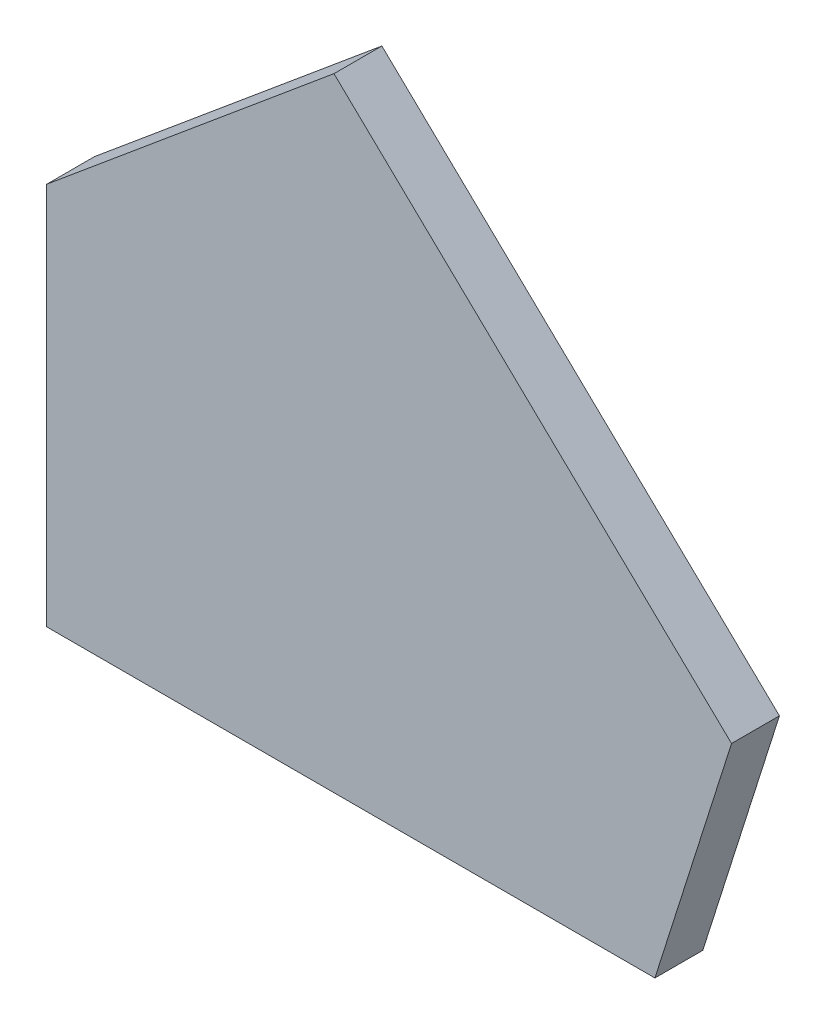
SolidWorks part; units mm, degrees
other "Детальный элемент1"
ref_plane "Спереди" through (0, 0, 0) normal (0, 0, 1) x (1, 0, 0)
ref_plane "Сверху" through (0, 0, 0) normal (0, 1, 0) x (1, 0, 0)
ref_plane "Справа" through (0, 0, 0) normal (1, 0, 0) x (0, 0, -1)
sketch "Эскиз1" plane through (0, 0, 0) normal (0, 0, 1) x (0, -1, 0)
  line L0 (0, -6.35) -> (0, 6.35)
  line L4 (0, -6.35) -> (-8, -6.35)
  line L5 (-8, -6.35) -> (-13, -0.35)
  line L6 (-13, -0.35) -> (-5.0401, 7.95)
  line L7 (-5.0401, 7.95) -> (0, 6.35)
  dimension "D1" = 14.3
  dimension "D2" = 12.7
  dimension "D3" = 6
  dimension "D4" = 8
  dimension "D5" = 5.0401
  dimension "D6" = 13
extrude "Бобышка-Вытянуть1" add sketch "Эскиз1" along normal blind 1
